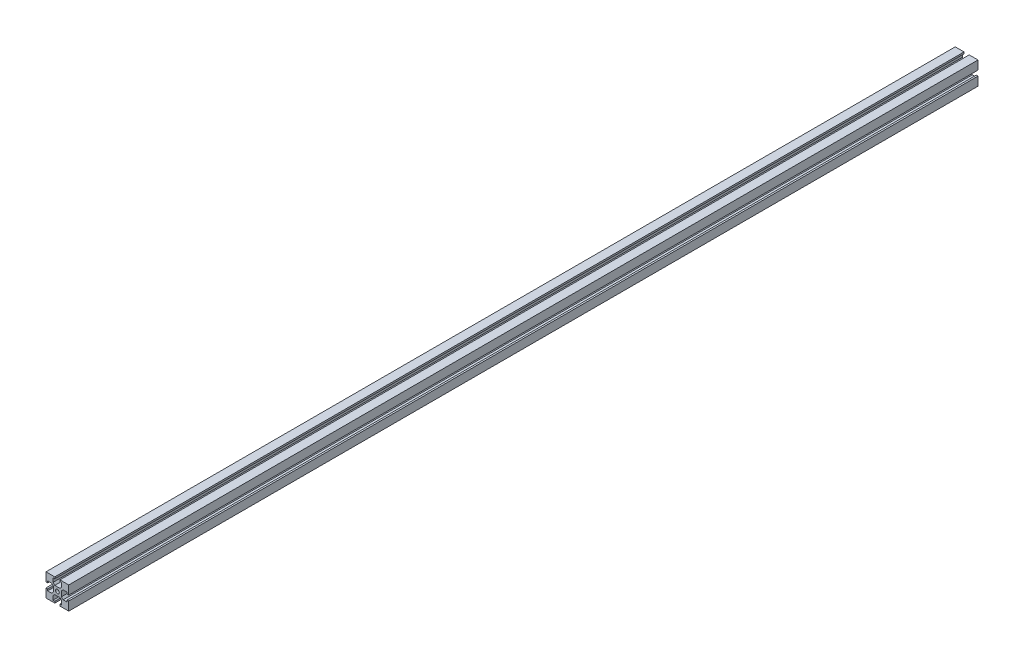
SolidWorks part; units mm, degrees
ref_plane "正面" through (0, 0, 0) normal (0, 0, 1) x (1, 0, 0)
ref_plane "平面" through (0, 0, 0) normal (0, 1, 0) x (1, 0, 0)
ref_plane "右側面" through (0, 0, 0) normal (1, 0, 0) x (0, 0, -1)
sketch "ｽｹｯﾁ2" plane through (0, 0, 0) normal (0, 0, 1) x (1, 0, 0)
  line L0 (0, 0) -> (0, 7.5) construction
  line L1 (-7.5, -7.5) -> (7.5, -7.5) construction
  line L2 (-7.5, -7.5) -> (-7.5, 7.5) construction
  line L3 (-7.5, 7.5) -> (7.5, 7.5) construction
  line L4 (7.5, -7.5) -> (7.5, 7.5) construction
  line L5 (-7.5, -7.5) -> (7.5, 7.5) construction
  line L6 (-7.5, 7.5) -> (7.5, -7.5) construction
  line L8 (1.7, 2.65) -> (-1.7, 2.65)
  line L9 (-2.85, 3.8) -> (2.85, 3.8) construction
  line L10 (-2.85, 6.4) -> (-2.85, 3.8)
  line L11 (2.85, 6.4) -> (2.85, 3.8)
  line L12 (-2.85, 3.8) -> (-1.7, 2.65)
  line L13 (1.7, 2.65) -> (2.85, 3.8)
  line L14 (-2.85, 6.4) -> (-1.7, 6.4)
  line L15 (-1.7, 6.4) -> (-1.7, 7.5)
  line L16 (-1.7, 7.5) -> (-7.5, 7.5)
  line L17 (2.85, 6.4) -> (1.7, 6.4)
  line L18 (1.7, 6.4) -> (1.7, 7.5)
  line L19 (1.7, 7.5) -> (7.5, 7.5)
  line L20 (3.8, 2.85) -> (2.65, 1.7)
  line L21 (2.65, -1.7) -> (2.65, 1.7)
  line L22 (2.65, -1.7) -> (3.8, -2.85)
  line L23 (6.4, -2.85) -> (6.4, -1.7)
  line L24 (6.4, -2.85) -> (3.8, -2.85)
  line L25 (6.4, -1.7) -> (7.5, -1.7)
  line L26 (7.5, -1.7) -> (7.5, -7.5)
  line L27 (6.4, 1.7) -> (7.5, 1.7)
  line L28 (7.5, 1.7) -> (7.5, 7.5)
  line L29 (6.4, 2.85) -> (6.4, 1.7)
  line L30 (6.4, 2.85) -> (3.8, 2.85)
  line L31 (2.85, -3.8) -> (1.7, -2.65)
  line L32 (-1.7, -2.65) -> (1.7, -2.65)
  line L33 (-1.7, -2.65) -> (-2.85, -3.8)
  line L34 (-2.85, -6.4) -> (-1.7, -6.4)
  line L35 (-2.85, -6.4) -> (-2.85, -3.8)
  line L36 (-1.7, -6.4) -> (-1.7, -7.5)
  line L37 (-1.7, -7.5) -> (-7.5, -7.5)
  line L38 (1.7, -6.4) -> (1.7, -7.5)
  line L39 (1.7, -7.5) -> (7.5, -7.5)
  line L40 (2.85, -6.4) -> (1.7, -6.4)
  line L41 (2.85, -6.4) -> (2.85, -3.8)
  line L42 (-3.8, -2.85) -> (-2.65, -1.7)
  line L43 (-2.65, 1.7) -> (-2.65, -1.7)
  line L44 (-2.65, 1.7) -> (-3.8, 2.85)
  line L45 (-6.4, 2.85) -> (-6.4, 1.7)
  line L46 (-6.4, 2.85) -> (-3.8, 2.85)
  line L47 (-6.4, 1.7) -> (-7.5, 1.7)
  line L48 (-7.5, 1.7) -> (-7.5, 7.5)
  line L49 (-6.4, -1.7) -> (-7.5, -1.7)
  line L50 (-7.5, -1.7) -> (-7.5, -7.5)
  line L51 (-6.4, -2.85) -> (-6.4, -1.7)
  line L52 (-6.4, -2.85) -> (-3.8, -2.85)
  circle A0 centre (0, 0) radius 1.25
  point P0 (0, 0)
  point P11 (0, 7.5)
  point P14 (0, 2.65)
  point P17 (0, 3.8)
  dimension "D8" = 2.5
  dimension "D1" = 15
  dimension "D2" = 3.4
  dimension "D3" = 1.1
  dimension "D4" = 2.6
  dimension "D5" = 5.7
  dimension "D6" = 3.4
  dimension "D7" = 4
extrude "ﾎﾞｽ - 押し出し1" add sketch "ｽｹｯﾁ2" along normal blind 600
